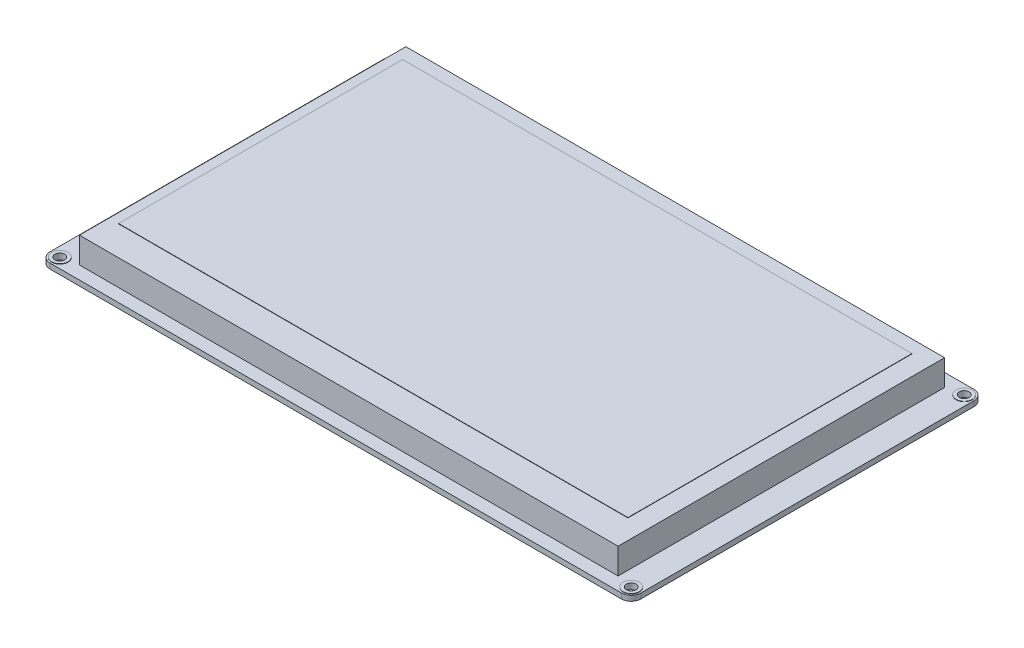
SolidWorks part; units mm, degrees
ref_plane "Front Plane" through (0, 0, 0) normal (0, 0, 1) x (1, 0, 0)
ref_plane "Top Plane" through (0, 0, 0) normal (0, 1, 0) x (1, 0, 0)
ref_plane "Right Plane" through (0, 0, 0) normal (1, 0, 0) x (0, 0, -1)
sketch "Sketch1" plane through (0, 0, 0) normal (0, 1, 0) x (1, 0, 0)
  line L1 (-87.5, -54) -> (87.5, -54)
  line L2 (-90.5, -51) -> (-90.5, 51)
  line L3 (-87.5, 54) -> (87.5, 54)
  line L4 (90.5, -51) -> (90.5, 51)
  line L5 (-90.5, -54) -> (90.5, 54) construction
  line L6 (-90.5, 54) -> (90.5, -54) construction
  arc A0 (90.5, -51) -> (87.5, -54) centre (87.5, -51) cw
  arc A1 (-87.5, -54) -> (-90.5, -51) centre (-87.5, -51) cw
  arc A2 (-87.5, 54) -> (-90.5, 51) centre (-87.5, 51) ccw
  arc A3 (90.5, 51) -> (87.5, 54) centre (87.5, 51) ccw
  point P0 (0, 0)
  dimension "D3" = 3
  dimension "D1" = 181
  dimension "D2" = 108
extrude "Boss-Extrude1" add sketch "Sketch1" along normal mid plane 1.6
sketch "Sketch2" plane through (0, 0.8, 0) normal (0, 1, 0) x (1, 0, 0)
  circle A0 centre (-87.5, 51) radius 1.5
  circle A1 centre (-87.5, -51) radius 1.5
  circle A2 centre (87.5, -51) radius 1.5
  circle A3 centre (87.5, 51) radius 1.5
  dimension "D1" = 3
extrude "Cut-Extrude1" cut sketch "Sketch2" against normal through all
sketch "Sketch3" plane through (0, 0.8, 0) normal (0, 1, 0) x (1, 0, 0)
  line L0 (0, 0) -> (0, 132.5627) construction
  line L1 (0, -55) -> (0, 55) construction
  line L2 (0, 0) -> (-184.5109, 0) construction
  line L3 (-55, 0) -> (55, 0) construction
  circle A0 centre (-87.5, 51) radius 2.5
  circle A1 centre (-87.5, 51) radius 1.5
  circle A2 centre (87.5, 51) radius 1.5
  circle A3 centre (87.5, 51) radius 2.5
  circle A4 centre (87.5, -51) radius 2.5
  circle A5 centre (87.5, -51) radius 1.5
  circle A6 centre (-87.5, -51) radius 1.5
  circle A7 centre (-87.5, -51) radius 2.5
  dimension "D1" = 5
extrude "Boss-Extrude2" add sketch "Sketch3" along normal blind 0.1
mirror "Mirror1" about plane through (0, 0, 0) normal (0, 1, 0) of "Boss-Extrude2"
sketch "Sketch4" plane through (0, 0.8, 0) normal (0, 1, 0) x (1, 0, 0)
  line L0 (90.5, -51) -> (90.5, 51) construction
  line L1 (-82.5, 50) -> (82.5, 50)
  line L2 (-82.5, 50) -> (-82.5, -50)
  line L3 (-82.5, -50) -> (82.5, -50)
  line L4 (82.5, 50) -> (82.5, -50)
  line L5 (-90.5, 51) -> (-90.5, -51) construction
  line L6 (87.5, 54) -> (-87.5, 54) construction
  line L7 (-87.5, -54) -> (87.5, -54) construction
  dimension "D1" = 8
  dimension "D2" = 8
  dimension "D3" = 4
  dimension "D4" = 4
extrude "Boss-Extrude3" add sketch "Sketch4" along normal blind 8 separate body
sketch "Sketch5" plane through (0, 8.8, 0) normal (0, 1, 0) x (1, 0, 0)
  line L0 (82.5, -50) -> (82.5, 50) construction
  line L1 (-79.5, 46) -> (76.5, 46)
  line L2 (-79.5, 46) -> (-79.5, -41)
  line L3 (-79.5, -41) -> (76.5, -41)
  line L4 (76.5, 46) -> (76.5, -41)
  line L6 (-82.5, 50) -> (-82.5, -50) construction
  line L7 (-82.5, -50) -> (82.5, -50) construction
  line L8 (82.5, 50) -> (-82.5, 50) construction
  dimension "D1" = 3
  dimension "D2" = 4
  dimension "D3" = 6
  dimension "D4" = 9
extrude "Cut-Extrude2" cut sketch "Sketch5" against normal blind 0.1 flip side to cut
sketch "Sketch6" plane through (0, -0.8, 0) normal (0, -1, 0) x (1, 0, 0)
  line L0 (5.335, 0) -> (-5.335, 0) construction
  line L1 (-82.5, -7.5) -> (-90.5, -7.5)
  line L2 (-82.5, -7.5) -> (-82.5, 7.5)
  line L3 (-82.5, 7.5) -> (-90.5, 7.5)
  line L4 (-90.5, -7.5) -> (-90.5, 7.5)
  line L5 (-82.5, -7.5) -> (-90.5, 7.5) construction
  line L6 (-82.5, 7.5) -> (-90.5, -7.5) construction
  line L7 (-90.5, -51) -> (-90.5, 51) construction
  point P0 (-86.5, 0)
  dimension "D1" = 8
  dimension "D2" = 15
extrude "Boss-Extrude4" add sketch "Sketch6" along normal blind 6 separate body
shell "Shell1" thickness 1
ref_plane "Plane1" through (-1.5, 0, 0) normal (-1, 0, 0) x (0, 0, 1)
ref_plane "Plane2" through (0, 0, -2.5) normal (0, 0, 1) x (1, 0, 0)
sketch "Sketch7"
sketch "Sketch9"
